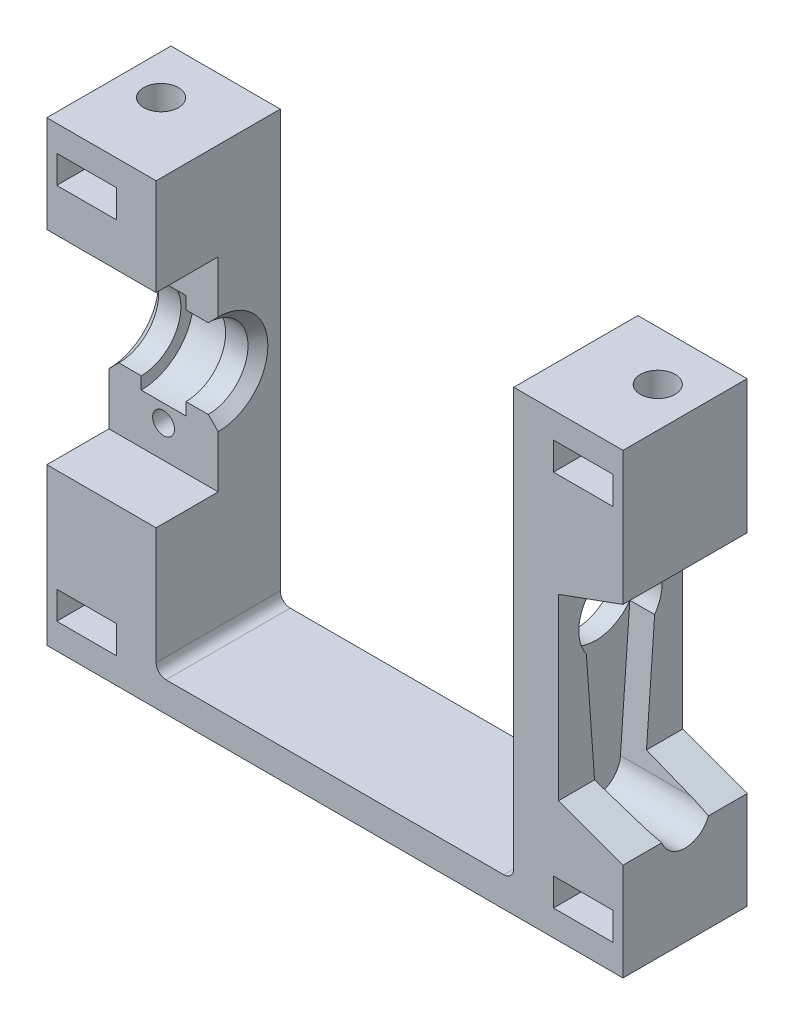
SolidWorks part; units mm, degrees
material "ABS"
ref_plane "Спереди" through (0, 0, 0) normal (0, 0, 1) x (1, 0, 0)
ref_plane "Сверху" through (0, 0, 0) normal (0, 1, 0) x (1, 0, 0)
ref_plane "Справа" through (0, 0, 0) normal (1, 0, 0) x (0, 0, -1)
sketch "Эскиз1" plane through (0, 0, 0) normal (0, 0, 1) x (1, 0, 0)
  line L1 (-29, -23) -> (29, -23)
  line L2 (-29, -23) -> (-29, 23)
  line L3 (-29, 23) -> (29, 23)
  line L4 (29, -23) -> (29, 23)
  line L5 (-29, -23) -> (29, 23) construction
  line L6 (-29, 23) -> (29, -23) construction
  point P0 (0, 0)
  dimension "D1" = 58
  dimension "D2" = 46
extrude "тело" add sketch "Эскиз1" along normal blind 12.5
sketch "Эскиз3" plane through (0, 0, 12.5) normal (0, 0, 1) x (1, 0, 0)
  line L1 (-18, -20) -> (18, -20)
  line L2 (-18, -20) -> (-18, 26)
  line L3 (-18, 26) -> (18, 26)
  line L4 (18, -20) -> (18, 26)
  line L5 (-29, -23) -> (29, -23) construction
  point P0 (0, 3)
  point P6 (0, -20)
  point P9 (-18, 3)
  point P10 (0, -23)
  dimension "D1" = 36
  dimension "D2" = 46
  dimension "D3" = 3
extrude "отверстие под серво" cut sketch "Эскиз3" against normal through all
sketch "Эскиз11" plane through (0, -23, 0) normal (0, -1, 0) x (1, 0, 0)
  line L0 (0, 12.5) -> (0, 0) construction
  line L1 (-29, 12.5) -> (29, 12.5) construction
  line L2 (-25, 5) -> (25, 5) construction
  line L3 (-29, 0) -> (29, 0) construction
  circle A0 centre (-25, 5) radius 1.75
  circle A1 centre (25, 5) radius 1.75
  point P8 (0, 5)
  dimension "D1" = 3.5
  dimension "D2" = 50
  dimension "D3" = 5
extrude "Крепежные отверстия сверху" cut sketch "Эскиз11" against normal blind 8
mirror "Крепежные отверстия снизу" about plane through (0, 0, 0) normal (0, 1, 0) of "Крепежные отверстия сверху"
sketch "Эскиз5" plane through (29, 0, 0) normal (1, 0, 0) x (0, 0, -1)
  line L0 (-9.2, 0.7667) -> (-8.2448, -12.4442) construction
  line L1 (-6.25, 3) -> (-6.25, -14.3) construction
  line L2 (-6.25, 6.7) -> (-6.25, -14.3) construction
  line L3 (-9.2, 0.7667) -> (-6.25, 0.7667) construction
  line L4 (-6.25, 0.7667) -> (-6.25, -14.3) construction
  line L5 (-3.3, 0.7667) -> (-4.2552, -12.4442) construction
  line L6 (-9.6884, 0.5881) -> (-8.7435, -12.4803)
  line L7 (-2.8116, 0.5881) -> (-3.7565, -12.4803)
  line L8 (-12.5, -23) -> (0, -23) construction
  line L11 (-12.5, 23) -> (0, 23) construction
  arc A0 (-2.8116, 0.5881) -> (-9.6884, 0.5881) centre (-6.25, 3) ccw
  arc A1 (-8.2448, -12.4442) -> (-4.2552, -12.4442) centre (-6.25, -12.3) ccw construction
  arc A2 (-8.7435, -12.4803) -> (-3.7565, -12.4803) centre (-6.25, -12.3) ccw
  arc A3 (-3.3, 0.7667) -> (-9.2, 0.7667) centre (-6.25, 3) ccw construction
  point P0 (-6.25, -23)
  dimension "D1" = 2.95
  dimension "D2" = 4
  dimension "D4" = 7.4
  dimension "D5" = 0.5
  dimension "D3" = 21
  dimension "D6" = 20
extrude "вырез под качалку" cut sketch "Эскиз5" against normal offset from surface (9 mm away) 2 up to face at (18, 1.5, 6.25)
sketch "Эскиз4" plane through (29, 0, 0) normal (1, 0, 0) x (0, 0, -1)
  line L0 (-6.25, 23) -> (-6.25, -23) construction
  line L1 (-12.5, 23) -> (0, 23) construction
  line L2 (-12.5, -23) -> (0, -23) construction
  line L4 (-12.5, -23) -> (-12.5, 23) construction
  line L5 (-12.5, 0) -> (0, 0) construction
  line L6 (0, -23) -> (0, 23) construction
  circle A0 centre (-6.25, 3) radius 4.2
  arc A1 (-2.8116, 0.5881) -> (-9.6884, 0.5881) centre (-6.25, 3) ccw construction
extrude "вырез под ось вращения" cut sketch "Эскиз4" against normal up to next
sketch "Эскиз6" plane through (-29, 0, 0) normal (-1, 0, 0) x (0, 0, 1)
  circle A0 centre (6.25, 3) radius 4
  dimension "D1" = 8
extrude "вырез под ось подшипника" cut sketch "Эскиз6" against normal up to surface (11 mm away) up to face at (-18, 1.5, 6.25)
sketch "Эскиз7" plane through (-29, 0, 0) normal (-1, 0, 0) x (0, 0, 1)
  line L0 (12.5, 23) -> (12.5, -23) construction
  line L1 (6.25, 13.25) -> (12.5, 13.25)
  line L2 (6.25, 13.25) -> (6.25, -7.25)
  line L3 (6.25, -7.25) -> (12.5, -7.25)
  line L4 (12.5, 13.25) -> (12.5, -7.25)
  point P6 (6.25, 3)
  point P7 (6.25, 3)
  dimension "D1" = 20.5
extrude "вырез под крепление подшипника" cut sketch "Эскиз7" against normal up to surface (11 mm away) up to face at (-18, 3, 10.25)
ref_plane "Плоскость1" through (-23.5, 0, 0) normal (-1, 0, 0) x (0, 0, 1)
sketch "Эскиз8" plane through (-23.5, 0, 0) normal (-1, 0, 0) x (0, 0, 1)
  circle A0 centre (6.25, 3) radius 5.25
  dimension "D1" = 10.5
extrude "вырез под подшипник" cut sketch "Эскиз8" against normal mid plane 4.5
sketch "Эскиз9" plane through (0, 0, 6.25) normal (0, 0, 1) x (1, 0, 0)
  line L1 (-29, 3) -> (-18, 3) construction
  line L3 (-29, 7) -> (-29, -1) construction
  line L4 (-18, -1) -> (-18, 7) construction
  line L5 (-23.5, -4) -> (-23.5, 10) construction
  circle A0 centre (-23.5, 10) radius 1.1
  circle A1 centre (-23.5, -4) radius 1.1
  point P9 (-23.5, 3)
  dimension "D1" = 2.2
  dimension "D2" = 14
extrude "отверстия под саморезы" cut sketch "Эскиз9" against normal offset from surface (5.25 mm away) 1 up to face at (0, 0.75, 0)
sketch "Эскиз10" plane through (0, 0, 12.5) normal (0, 0, 1) x (1, 0, 0)
  line L1 (29, -23) -> (29, 23) construction
  line L2 (18, -20) -> (18, 23) construction
  line L3 (29, -13.1658) -> (29, 9.5658)
  line L4 (22.5, -10.8) -> (22.5, 7.2)
  line L5 (29, 9.5658) -> (22.5, 7.2)
  line L6 (22.5, -10.8) -> (29, -13.1658)
  line L8 (29, 7.2) -> (18, 7.2) construction
  dimension "D1" = 70
  dimension "D2" = 4.5
  dimension "D3" = 18
  dimension "D4" = 70
extrude "вырез чтобы вставлять качалку" cut sketch "Эскиз10" against normal through all
chamfer "Фаска1" distance 1 angle 45 2 edges at (-29, 3, 2.25) (-18, 3, 2.25)
fillet "Скругление1" radius 1 2 edges at (18, -20, 6.25) (-18, -20, 6.25)
sketch "Эскиз12" plane through (0, 0, 0) normal (0, 0, 1) x (1, 0, 0)
  line L0 (-17, -20) -> (17, -20) construction
  line L1 (-10, -20) -> (10, -20)
  line L2 (-10, -20) -> (-10, -21.5)
  line L3 (-10, -21.5) -> (10, -21.5)
  line L4 (10, -20) -> (10, -21.5)
  point P6 (0, -20)
  dimension "D1" = 20
  dimension "D2" = 1.5
extrude "вырез под шлейф" [suppressed] cut sketch "Эскиз12" along normal through all
fillet "Скругление2" [suppressed] radius 0.5
sketch "Эскиз13" [suppressed] plane through (0, 0, 12.5) normal (0, 0, 1) x (1, 0, 0)
  line L1 (-18, 24) -> (18, 24)
  line L2 (-18, 24) -> (-18, 23)
  line L3 (-18, 23) -> (18, 23)
  line L4 (18, 24) -> (18, 23)
  line L5 (29, 23) -> (18, 23) construction
extrude "Удаление нижней перекладины" [suppressed] cut sketch "Эскиз13" against normal up to next
sketch "Эскиз14" plane through (0, 23, 0) normal (0, 1, 0) x (1, 0, 0)
  line L0 (-29, -12.5) -> (-29, -28)
  line L1 (0, 0) -> (0, -28) construction
  line L2 (-29, -12.5) -> (-18, -12.5)
  line L3 (-18, -12.5) -> (-18, -24.5)
  line L4 (-18, -24.5) -> (18, -24.5)
  line L5 (-29, -28) -> (29, -28)
  line L6 (18, -12.5) -> (18, -24.5)
  line L7 (29, -12.5) -> (18, -12.5)
  line L8 (29, -12.5) -> (29, -28)
  point P13 (0, -24.5)
  dimension "D1" = 15.5
  dimension "D2" = 12
extrude "Нижняя скоба жесткости" [suppressed] add sketch "Эскиз14" against normal blind 5
fillet "Скругление3" [suppressed] radius 10
fillet "Скругление4" [suppressed] radius 1.5
sketch "Эскиз15" [suppressed] plane through (0, 0, 0) normal (0, 0, -1) x (-1, 0, 0)
  line L0 (0, 23) -> (0, 0) construction
  line L1 (-18, 23) -> (18, 23) construction
  line L2 (-29, 23) -> (-18, 23) construction
  line L4 (-27.7202, 9.1) -> (-29, 9.5658)
  line L5 (-34, 23) -> (-29, 23)
  line L6 (-29, 9.5658) -> (-29, 23) construction
  line L7 (-29, 9.5658) -> (-22.5, 7.2) construction
  line L8 (-29, 9.5658) -> (-29, 23)
  line L9 (-34, 16.05) -> (-29, 16.05) construction
  line L10 (-34, 9.1) -> (-27.7202, 9.1)
  line L11 (34, 9.1) -> (29, 9.1)
  line L12 (34, 23) -> (29, 23)
  line L13 (29, 23) -> (29, -23) construction
  line L14 (29, 23) -> (29, 9.1)
  arc A0 (-36.5156, 11.2153) -> (-36.5156, 20.8847) centre (-34, 16.05) ccw
  arc A1 (-34, 23) -> (-37.208, 22.2153) centre (-34, 16.05) ccw
  arc A2 (-37.208, 22.2153) -> (-36.5156, 20.8847) centre (-36.8618, 21.55) ccw
  arc A4 (-37.208, 9.8847) -> (-36.5156, 11.2153) centre (-36.8618, 10.55) cw
  arc A5 (-37.208, 9.8847) -> (-34, 9.1) centre (-34, 16.05) ccw
  arc A6 (37.208, 9.8847) -> (34, 9.1) centre (34, 16.05) cw
  arc A7 (37.208, 9.8847) -> (36.5156, 11.2153) centre (36.8618, 10.55) ccw
  arc A8 (34, 23) -> (37.208, 22.2153) centre (34, 16.05) cw
  arc A9 (37.208, 22.2153) -> (36.5156, 20.8847) centre (36.8618, 21.55) cw
  arc A10 (36.5156, 11.2153) -> (36.5156, 20.8847) centre (34, 16.05) cw
  dimension "D1" = 10.9
  dimension "D2" = 1.5
  dimension "D3" = 34
  dimension "D4" = 11
extrude "Крепление фар" [suppressed] add sketch "Эскиз15" against normal blind 12.5
fillet "Скругление5" [suppressed] radius 1
sketch "Эскиз17" plane through (0, 23, 0) normal (0, 1, 0) x (1, 0, 0)
  line L1 (22, -3.2679) -> (22, -6.7321)
  line L2 (22, -6.7321) -> (25, -8.4641)
  line L3 (25, -8.4641) -> (28, -6.7321)
  line L4 (28, -6.7321) -> (28, -3.2679)
  line L5 (28, -3.2679) -> (25, -1.5359)
  line L6 (25, -1.5359) -> (22, -3.2679)
  circle A0 centre (25, -5) radius 3 construction
  dimension "D1" = 6
extrude "Под гайки" cut sketch "Эскиз17" against normal mid plane 2.8 from offset 4 offset against normal yes
sketch "Эскиз18" plane through (29, 0, 12.5) normal (0, 0, 1) x (1, 0, 0)
  line L1 (-1, 20.4) -> (-7, 20.4)
  line L2 (-1, 20.4) -> (-1, 17.6)
  line L3 (-1, 17.6) -> (-7, 17.6)
  line L4 (-7, 20.4) -> (-7, 17.6)
extrude "Для вставки гайки" cut sketch "Эскиз18" against normal up to next
mirror "Зеркальное отражение1" about plane through (0, 0, 0) normal (1, 0, 0) of "Для вставки гайки", "Под гайки"
mirror "Зеркальное отражение2" about plane through (0, 0, 0) normal (0, 1, 0) of "Зеркальное отражение1", "Для вставки гайки", "Под гайки"
sketch "Эскиз19" plane through (0, 0, 12.5) normal (0, 0, 1) x (1, 0, 0)
  line L0 (31.3707, 11.4653) -> (11.652, 11.4653)
  line L1 (11.652, 11.4653) -> (-24.0509, 27.3)
  line L2 (-24.0509, 27.3) -> (-36.2257, 27.3)
  line L3 (-36.2257, 27.3) -> (-36.2257, -26.6278)
  line L4 (-36.2257, -26.6278) -> (31.3707, -25.5821)
  line L5 (31.3707, -25.5821) -> (31.3707, 11.4653)
extrude "Вырез-Вытянуть1" [suppressed] cut sketch "Эскиз19" against normal through all
